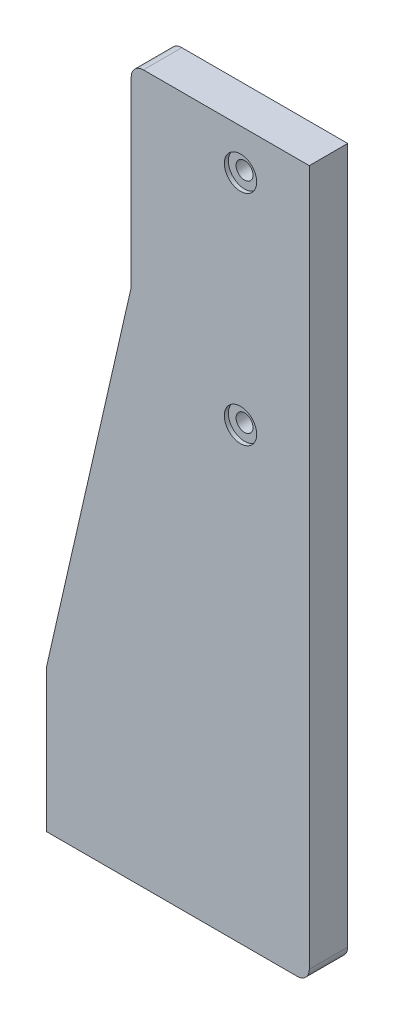
SolidWorks part; units mm, degrees
ref_plane "前视基准面" through (0, 0, 0) normal (0, 0, 1) x (1, 0, 0)
ref_plane "上视基准面" through (0, 0, 0) normal (0, 1, 0) x (1, 0, 0)
ref_plane "右视基准面" through (0, 0, 0) normal (1, 0, 0) x (0, 0, -1)
sketch "草图10" plane through (0, 0, 0) normal (0, 0, 1) x (1, 0, 0)
  line L0 (0, 0) -> (65, 0)
  line L1 (65, 0) -> (65, 175)
  line L2 (65, 175) -> (21, 175)
  line L3 (21, 175) -> (21, 127)
  line L4 (21, 127) -> (0, 35)
  line L5 (0, 35) -> (0, 0)
  line L6 (49, 175) -> (49, 0) construction
  dimension "D1" = 65
  dimension "D2" = 175
  dimension "D3" = 44
  dimension "D4" = 48
  dimension "D5" = 35
  dimension "D6" = 16
extrude "凸台-拉伸4" add sketch "草图10" along normal blind 9.5 contours L4 L5 L0 L1 L2 L3
sketch "草图11" plane through (0, 0, 9.5) normal (0, 0, 1) x (1, 0, 0)
  line L0 (48, 175) -> (48, 0) construction
  line L1 (65, 175) -> (21, 175) construction
  line L2 (0, 0) -> (65, 0) construction
  line L3 (65, 0) -> (65, 175) construction
  circle A0 centre (48, 165) radius 2.1
  circle A1 centre (48, 111) radius 2.1
  dimension "D1" = 4.2
  dimension "D2" = 10
  dimension "D3" = 54
  dimension "D4" = 17
extrude "切除-拉伸8" cut sketch "草图11" against normal through all contours A1 | A0
sketch "草图12" plane through (0, 0, 9.5) normal (0, 0, 1) x (1, 0, 0)
  circle A0 centre (48, 165) radius 4
  circle A1 centre (48, 111) radius 4
  dimension "D1" = 8
extrude "切除-拉伸9" cut sketch "草图12" against normal blind 1
fillet "圆角7" radius 3 3 edges at (65, 0, 4.75) (21, 127, 4.75) (21, 175, 4.75)
sketch "草图13" plane through (0, 0, 9.5) normal (0, 0, 1) x (1, 0, 0)
  line L0 (48, 165) -> (48, 51.4877) construction
